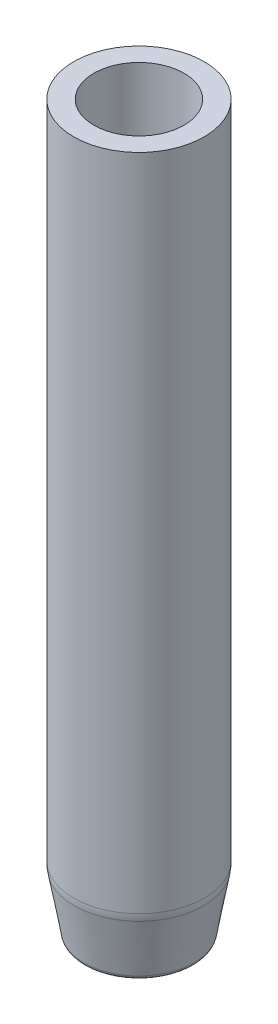
SolidWorks part; units mm, degrees
material "Gray Cast Iron (SN)"
ref_plane "Front Plane" through (0, 0, 0) normal (0, 0, 1) x (1, 0, 0)
ref_plane "Top Plane" through (0, 0, 0) normal (0, 1, 0) x (1, 0, 0)
ref_plane "Right Plane" through (0, 0, 0) normal (1, 0, 0) x (0, 0, -1)
sketch "Sketch1" plane through (0, 0, 0) normal (0, 0, 1) x (1, 0, 0)
  line L0 (0, 28.575) -> (0, -28.575) construction
  line L1 (-3.556, 28.575) -> (-5.1435, 28.575)
  line L2 (-5.1435, 28.575) -> (-5.1435, -23.435)
  line L3 (-5.0953, -23.9863) -> (-4.3437, -28.2486)
  line L4 (-3.9183, -28.575) -> (0, -28.575) construction
  line L5 (-3.556, 28.575) -> (-3.556, -28.1796)
  arc A0 (-3.556, -28.1796) -> (-4.3437, -28.2486) centre (-3.9529, -28.1796) cw
  arc A1 (-5.1435, -23.435) -> (-5.0953, -23.9863) centre (-1.9685, -23.435) ccw
  point P7 (-3.556, -32.7159)
  point P8 (0, 0)
  dimension "D4" = 0.3969
  dimension "D5" = 3.175
  dimension "D1" = 5.1435
  dimension "D2" = 3.556
  dimension "D3" = 10
  dimension "D6" = 57.15
revolve "Revolve1" add sketch "Sketch1" angle 360 about L0
